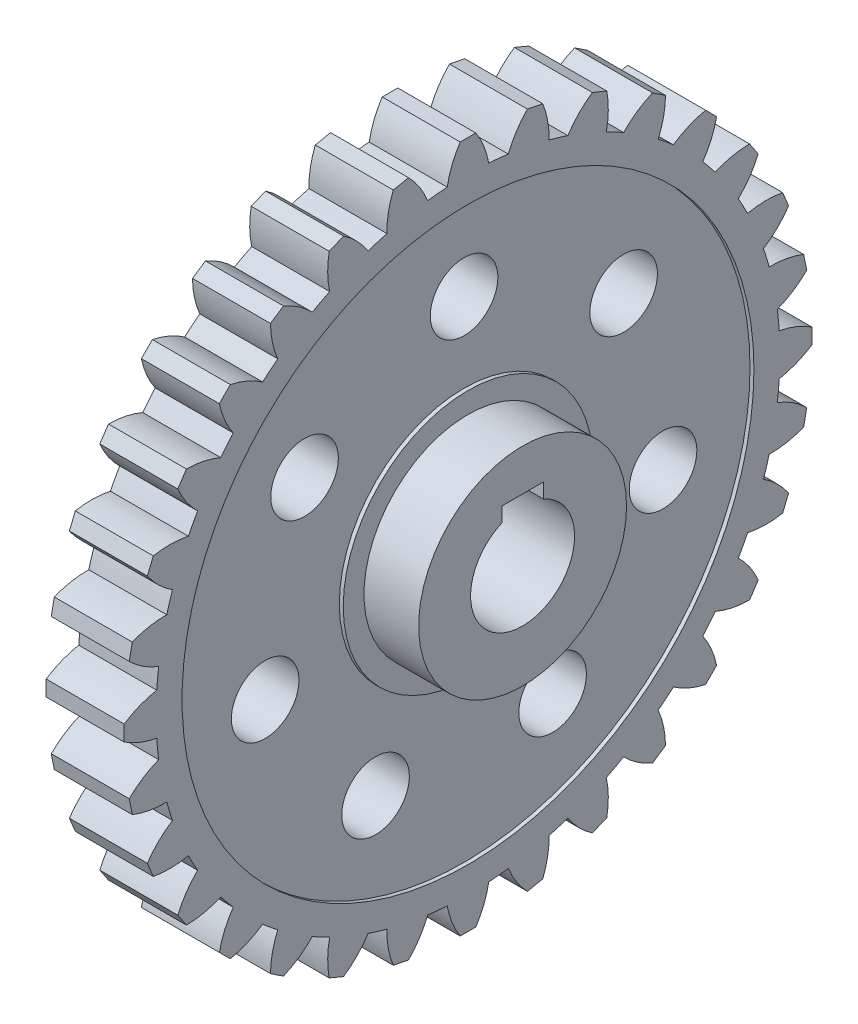
SolidWorks part; units mm, degrees
material "Brass"
ref_plane "Front Plane" through (0, 0, 0) normal (0, 0, 1) x (1, 0, 0)
ref_plane "Top Plane" through (0, 0, 0) normal (0, 1, 0) x (1, 0, 0)
ref_plane "Right Plane" through (0, 0, 0) normal (1, 0, 0) x (0, 0, -1)
sketch "Sketch1" plane through (0, 0, 0) normal (1, 0, 0) x (0, 0, -1)
  circle A0 centre (0, 0) radius 240
  dimension "D1" = 480
extrude "Boss-Extrude1" add sketch "Sketch1" along normal mid plane 60
sketch "Sketch2" plane through (30, 0, 0) normal (1, 0, 0) x (0, 0, -1)
  line L0 (0, 0) -> (0, 75.3723) construction
  line L1 (-6, 264.5461) -> (6, 264.5461)
  arc A0 (-16, 239.4661) -> (16, 239.4661) centre (0, 0) cw
  circle A1 centre (0, 0) radius 240 construction
  arc A4 (-6, 264.5461) -> (-16, 239.4661) centre (50.9069, 227.3223) ccw
  arc A5 (6, 264.5461) -> (16, 239.4661) centre (-50.9069, 227.3223) cw
  dimension "D4" = 68
  dimension "D1" = 6
  dimension "D2" = 25.08
  dimension "D3" = 16
extrude "Boss-Extrude2" add sketch "Sketch2" against normal up to surface (60 mm away) up to face at (-30, 0, -240)
pattern_circular "CirPattern1" count 32 over 360 about axis through (0, 0, 0) along (1, 0, 0) of "Boss-Extrude2"
sketch "Sketch3" plane through (0, 0, 0) normal (1, 0, 0) x (0, 0, -1)
  circle A0 centre (0, 0) radius 80
  dimension "D1" = 160
extrude "Boss-Extrude3" add sketch "Sketch3" along normal mid plane 144
sketch "Sketch4" plane through (72, 0, 0) normal (1, 0, 0) x (0, 0, -1)
  line L0 (0, 0) -> (0, 13.8261) construction
  line L1 (-16, 48) -> (16, 48)
  line L2 (-16, 48) -> (-16, 36.6606)
  line L3 (16, 48) -> (16, 36.6606)
  arc A0 (-16, 36.6606) -> (16, 36.6606) centre (0, 0) ccw
  dimension "D1" = 80
  dimension "D2" = 32
  dimension "D3" = 48
extrude "Cut-Extrude1" cut sketch "Sketch4" against normal through all
sketch "Sketch5" plane through (30, 0, 0) normal (1, 0, 0) x (0, 0, -1)
  circle A0 centre (0, 0) radius 96
  circle A1 centre (0, 0) radius 220
  dimension "D1" = 440
  dimension "D2" = 192
extrude "Cut-Extrude2" cut sketch "Sketch5" against normal blind 3
sketch "Sketch6" plane through (27, 0, 0) normal (1, 0, 0) x (0, 0, -1)
  circle A0 centre (0, 0) radius 157 construction
  circle A1 centre (0, 157) radius 26
  dimension "D1" = 314
  dimension "D2" = 52
extrude "Cut-Extrude3" cut sketch "Sketch6" against normal through all
pattern_circular "CirPattern2" count 7 over 360 about axis through (0, 0, 0) along (1, 0, 0) of "Cut-Extrude3"
